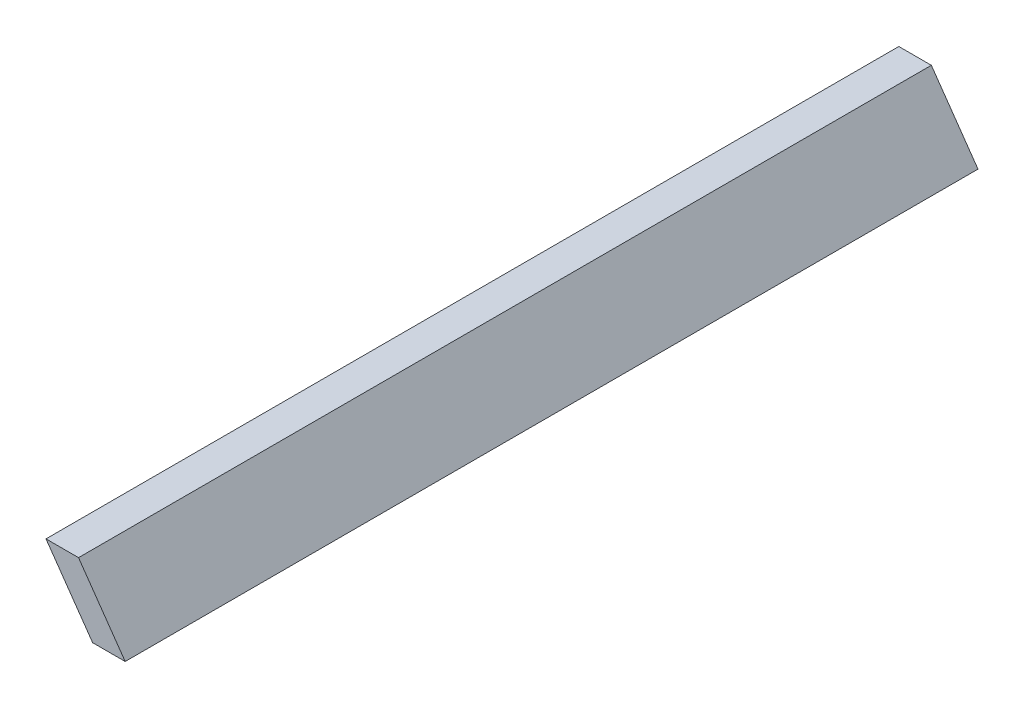
SolidWorks part; units mm, degrees
material "Gray Cast Iron"
ref_plane "Front Plane" through (0, 0, 0) normal (0, 0, 1) x (1, 0, 0)
ref_plane "Top Plane" through (0, 0, 0) normal (0, 1, 0) x (1, 0, 0)
ref_plane "Right Plane" through (0, 0, 0) normal (1, 0, 0) x (0, 0, -1)
sketch "Sketch6" plane through (0, 0, 0) normal (0, 0, 1) x (1, 0, 0)
  line B0 (-34.7427, -15.875) -> (92.2573, -15.875)
  line B1 (92.2573, 0) -> (65.2665, 0)
  line B2 (-11.1158, 15.875) -> (0, 0)
  line B3 (0, 0) -> (-34.7427, 0)
  line B4 (-7.7519, 0) -> (-18.8677, 15.875)
  line B5 (-18.8677, 15.875) -> (-11.1158, 15.875)
  line B6 (12.701, 15.875) -> (12.701, -3.175)
  line B7 (12.701, -3.175) -> (44.8136, -3.175)
  line B8 (12.701, 15.875) -> (-11.1158, 15.875)
  line B9 (-34.7427, 0) -> (-34.7427, 31.75)
  line B10 (-34.7427, 31.75) -> (92.2573, 31.75)
  line B11 (92.2573, 31.75) -> (92.2573, 0)
  line B12 (28.7573, 31.75) -> (28.7573, -15.875) construction
  line B13 (-7.7519, 0) -> (65.2665, 0) construction
  line B14 (0.0553, 21.082) -> (57.4593, 21.082) construction
  line B15 (3.3573, -8.001) -> (54.1573, -8.001) construction
  line B16 (3.3573, -8.001) -> (3.3573, 7.9375) construction
  line B17 (54.1573, -8.001) -> (54.1573, 7.9375) construction
  line B18 (-24.0747, 7.9375) -> (81.5893, 7.9375) construction
  circle B19 centre (28.7573, 6.35) radius 18.669 construction
sketch_block_instance "dovetail pair-1"
sketch_block "dovetail pair" parameters "D8"=37.338, "D1"=55, "D2"=127, "D3"=6.35, "D4"=15.875, "D5"=31.75, "D6"=95.25, "D7"=19.05, "D9"=55, "D10"=31.75, "D11"=50.8, "D12"=23.876, "D13"=7.874, "D14"=10.668, "D15"=34.798, "D16"=21.082, "D17"=7.9375
sketch "end-profile" plane through (0, 0, 0) normal (0, 0, 1) x (1, 0, 0)
  line L0 (0, 0) -> (-7.7519, 0)
  line L4 (-11.1158, 15.875) -> (0, 0) construction
  line L5 (-18.8677, 15.875) -> (-11.1158, 15.875) construction
  line L6 (-7.7519, 0) -> (-18.8677, 15.875) construction
  line L7 (-11.1158, 15.875) -> (0, 0)
  line L8 (-18.8677, 15.875) -> (-11.1158, 15.875)
  line L9 (-7.7519, 0) -> (-18.8677, 15.875)
extrude "Boss-Extrude1" add sketch "end-profile" along normal blind 203.2
ref_plane "screw pocket Plane1" through (-18.8677, 0, 0) normal (1, 0, 0) x (0, 0, -1)
sketch "Sketch4" plane through (-18.8677, 0, 0) normal (1, 0, 0) x (0, 0, -1)
  line L0 (0, 7.9375) -> (-201.1082, 7.9375) construction
  line L3 (-180.1412, 7.9375) -> (-180.1412, 0)
  line L4 (-180.1412, 0) -> (-173.367, 0)
  line L5 (-173.367, 0) -> (-173.367, 7.9375)
  line L6 (-142.0412, 7.9375) -> (-142.0412, 0)
  line L7 (-142.0412, 0) -> (-135.267, 0)
  line L8 (-135.267, 0) -> (-135.267, 7.9375)
  line L9 (-103.9412, 7.9375) -> (-103.9412, 0)
  line L10 (-103.9412, 0) -> (-97.167, 0)
  line L11 (-97.167, 0) -> (-97.167, 7.9375)
  line L12 (-65.8412, 7.9375) -> (-65.8412, 0)
  line L13 (-65.8412, 0) -> (-59.067, 0)
  line L14 (-59.067, 0) -> (-59.067, 7.9375)
  line L15 (-27.7412, 7.9375) -> (-27.7412, 0)
  line L16 (-27.7412, 0) -> (-20.967, 0)
  line L17 (-20.967, 0) -> (-20.967, 7.9375)
  line L18 (-180.1412, 7.9375) -> (-142.0412, 7.9375) construction
  line L19 (-203.2, 0) -> (0, 0) construction
  line L21 (0, 0) -> (0, 15.875) construction
  arc A0 (-173.367, 7.9375) -> (-180.1412, 7.9375) centre (-176.7541, 7.9375) ccw
  arc A1 (-135.267, 7.9375) -> (-142.0412, 7.9375) centre (-138.6541, 7.9375) ccw
  arc A2 (-97.167, 7.9375) -> (-103.9412, 7.9375) centre (-100.5541, 7.9375) ccw
  arc A3 (-59.067, 7.9375) -> (-65.8412, 7.9375) centre (-62.4541, 7.9375) ccw
  arc A4 (-20.967, 7.9375) -> (-27.7412, 7.9375) centre (-24.3541, 7.9375) ccw
  dimension "D1" = 6.7742
  dimension "D2" = 38.1
  dimension "D3" = 5
extrude "Cut-Extrude1" cut sketch "Sketch4" along normal blind 7.112
sketch "Sketch5" [suppressed] plane through (-18.8677, 0, 0) normal (1, 0, 0) x (0, 0, -1)
  line L0 (0, 7.9375) -> (-127, 7.9375) construction
  line L3 (-104.9871, 7.9375) -> (-104.9871, 0)
  line L5 (-104.9871, 0) -> (-98.2129, 0)
  line L6 (-98.2129, 0) -> (-98.2129, 7.9375)
  line L7 (-66.8871, 7.9375) -> (-66.8871, 0)
  line L8 (-66.8871, 0) -> (-60.1129, 0)
  line L9 (-60.1129, 0) -> (-60.1129, 7.9375)
  line L10 (-28.7871, 7.9375) -> (-28.7871, 0)
  line L11 (-28.7871, 0) -> (-22.0129, 0)
  line L12 (-22.0129, 0) -> (-22.0129, 7.9375)
  line L13 (-104.9871, 7.9375) -> (-66.8871, 7.9375) construction
  line L14 (-127, 0) -> (-127, 15.875) construction
  line L15 (-127, 0) -> (0, 0) construction
  line L16 (0, 0) -> (0, 15.875) construction
  arc A0 (-98.2129, 7.9375) -> (-104.9871, 7.9375) centre (-101.6, 7.9375) ccw
  arc A1 (-60.1129, 7.9375) -> (-66.8871, 7.9375) centre (-63.5, 7.9375) ccw
  arc A2 (-22.0129, 7.9375) -> (-28.7871, 7.9375) centre (-25.4, 7.9375) ccw
  dimension "D1" = 6.7742
  dimension "D2" = 38.1
extrude "Cut-Extrude2" [suppressed] cut sketch "Sketch5" along normal blind 7.112
equation "\"dovetail-angle\"= 55"
equation "\"dovetail-stock-width\"= 5"
equation "\"dovetail-stock-height\"= 1.25"
equation "\"dovetail-depth\"= 0.5 * \"dovetail-stock-height\""
equation "\"dovetail-throat-width\"= \"dovetail-stock-width\" - (2 * \"dovetail-depth\")"
equation "\"delta-x\"= 6"
equation "\"delta-y\"= 3"
equation "\"delta-z\"= 2.5"
equation "\"acme-nut-height\"= 0.5"
equation "\"acme-nut-width\"= 0.75"
equation "\"gib-thickness\"= 0.25"
equation "\"x-slide-length\"= \"dovetail-stock-width\" + \"delta-x\""
equation "\"y-slide-length\"= \"dovetail-stock-width\" + \"delta-y\""
equation "\"dog-point-diam\"= .149"
equation "\"dog-point-length\"= .067"
equation "\"dovetail-double-height\"= 2 * \"dovetail-depth\" + 0.5"
equation "\"acme-major-diam\"= .5"
equation "\"acme-pitch-diam\"= 0.45"
equation "\"acme-minor-diam\"= 0.4"
equation "\"acme-nut-od\"= 1.47"
equation "\"acme-nut-length\"= 1"
equation "\"acme-nut-trim-height\"= .75"
equation "\"screw-bearing-od\"= 0.5"
equation "\"screw-bearing-length\"= .375"
equation "\"screw-bearing-id\"= .375"
equation "\"end-plate-thickness\"= \"screw-bearing-length\""
equation "\"screw-add-length\"= 2 * \"end-plate-thickness\" + 1 + 0.5"
equation "\"x-screw-length\"= \"x-slide-length\" + \"screw-add-length\""
equation "\"y-screw-length\"= \"y-slide-length\" + \"screw-add-length\""
equation "\"acme-nut-mount-hole-space-horz\"= 0.95"
equation "\"acme-nut-mount-hole-space-vert\"= 0.5 * \"acme-nut-length\""
equation "\"vise-hole-center-dist\"= 6.75"
equation "\"wiper_plate_clearance\"= .03"
equation "\"dial-width\"= 0.5"
equation "\"quarter-twenty-free-fit\"= .2667"
equation "\"D1@Sketch4\"=\"quarter-twenty-free-fit\""
equation "\"D1@Sketch5\"=\"quarter-twenty-free-fit\""
equation "\"D2@dovetail pair\"=\"dovetail-stock-width\""
equation "\"D1@dovetail pair\"=\"dovetail-angle\""
equation "\"D3@dovetail pair\"=\"gib-thickness\""
equation "\"D4@dovetail pair\"=\"dovetail-depth\""
equation "\"D5@dovetail pair\"=\"dovetail-stock-height\""
equation "\"D6@dovetail pair\"=\"dovetail-throat-width\""
equation "\"D10@dovetail pair\"=\"dovetail-stock-height\""
equation "\"D7@dovetail pair\"=\"acme-nut-trim-height\""
equation "\"D8@dovetail pair\"=\"acme-nut-od\""
equation "\"D9@dovetail pair\"=\"dovetail-angle\""
equation "\"D17@dovetail pair\"=\"dovetail-depth\"/2"
equation "\"acme-nut-trim-width\"= 1.25"
equation "\"acme_nut_clearance\"= .01"
equation "\"dovetail_male_clearance\"= .01"
